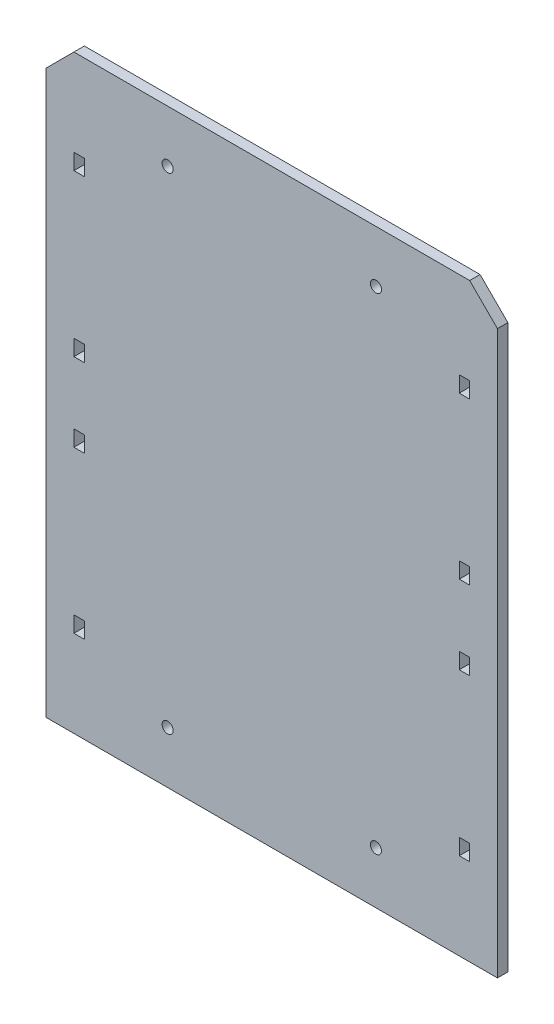
SolidWorks part; units mm, degrees
ref_plane "正面" through (0, 0, 0) normal (0, 0, 1) x (1, 0, 0)
ref_plane "平面" through (0, 0, 0) normal (0, 1, 0) x (1, 0, 0)
ref_plane "右側面" through (0, 0, 0) normal (1, 0, 0) x (0, 0, -1)
sketch "ｽｹｯﾁ1" plane through (0, 0, 0) normal (0, 0, 1) x (1, 0, 0)
  line L0 (0, 162) -> (8, 170)
  line L1 (0, 0) -> (130, 0)
  line L2 (0, 0) -> (0, 162)
  line L3 (8, 170) -> (122, 170)
  line L4 (130, 0) -> (130, 162)
  line L5 (8, 145) -> (11, 145)
  line L6 (8, 145) -> (8, 140.4)
  line L7 (8, 140.4) -> (11, 140.4)
  line L8 (11, 145) -> (11, 140.4)
  line L9 (122, 145) -> (119, 145)
  line L10 (122, 145) -> (122, 140.4)
  line L11 (122, 140.4) -> (119, 140.4)
  line L12 (119, 145) -> (119, 140.4)
  line L13 (8, 29.6) -> (11, 29.6)
  line L14 (8, 29.6) -> (8, 25)
  line L15 (8, 25) -> (11, 25)
  line L16 (11, 29.6) -> (11, 25)
  line L17 (119, 29.6) -> (122, 29.6)
  line L18 (119, 29.6) -> (119, 25)
  line L19 (119, 25) -> (122, 25)
  line L20 (122, 29.6) -> (122, 25)
  line L21 (8, 98.6) -> (11, 98.6)
  line L22 (8, 98.6) -> (8, 94)
  line L23 (8, 94) -> (11, 94)
  line L24 (11, 98.6) -> (11, 94)
  line L25 (119, 98.6) -> (122, 98.6)
  line L26 (119, 98.6) -> (119, 94)
  line L27 (119, 94) -> (122, 94)
  line L28 (122, 98.6) -> (122, 94)
  line L29 (8, 76) -> (11, 76)
  line L30 (8, 76) -> (8, 71.4)
  line L31 (8, 71.4) -> (11, 71.4)
  line L32 (11, 76) -> (11, 71.4)
  line L33 (119, 76) -> (122, 76)
  line L34 (119, 76) -> (119, 71.4)
  line L35 (119, 71.4) -> (122, 71.4)
  line L36 (122, 76) -> (122, 71.4)
  line L37 (122, 170) -> (130, 162)
  circle A0 centre (35, 155) radius 1.6
  circle A1 centre (95, 155) radius 1.6
  circle A2 centre (35, 15) radius 1.6
  circle A3 centre (95, 15) radius 1.6
  point P21 (119, 142.7)
  point P38 (8, 27.3)
  point P39 (9.5, 25)
  dimension "D40" = 3.2
  dimension "D41" = 3.2
  dimension "D42" = 3.2
  dimension "D43" = 3.2
  dimension "D1" = 170
  dimension "D3" = 3
  dimension "D4" = 4.6
  dimension "D5" = 3
  dimension "D6" = 4.6
  dimension "D7" = 3
  dimension "D8" = 4.6
  dimension "D9" = 3
  dimension "D10" = 4.6
  dimension "D11" = 3
  dimension "D12" = 4.6
  dimension "D13" = 3
  dimension "D14" = 4.6
  dimension "D15" = 4.6
  dimension "D16" = 3
  dimension "D17" = 3
  dimension "D18" = 4.6
  dimension "D19" = 51
  dimension "D20" = 51
  dimension "D21" = 8
  dimension "D22" = 8
  dimension "D23" = 8
  dimension "D24" = 8
  dimension "D25" = 8
  dimension "D26" = 8
  dimension "D27" = 51
  dimension "D28" = 51
  dimension "D29" = 8
  dimension "D30" = 8
  dimension "D31" = 25
  dimension "D32" = 25
  dimension "D33" = 25
  dimension "D34" = 25
  dimension "D35" = 130
  dimension "D36" = 8
  dimension "D37" = 11.3137
  dimension "D38" = 11.3137
  dimension "D39" = 45
  dimension "D44" = 35
  dimension "D45" = 35
  dimension "D46" = 35
  dimension "D47" = 35
  dimension "D48" = 140
  dimension "D49" = 140
  dimension "D50" = 15
  dimension "D51" = 15
extrude "ﾎﾞｽ - 押し出し1" add sketch "ｽｹｯﾁ1" along normal blind 3
